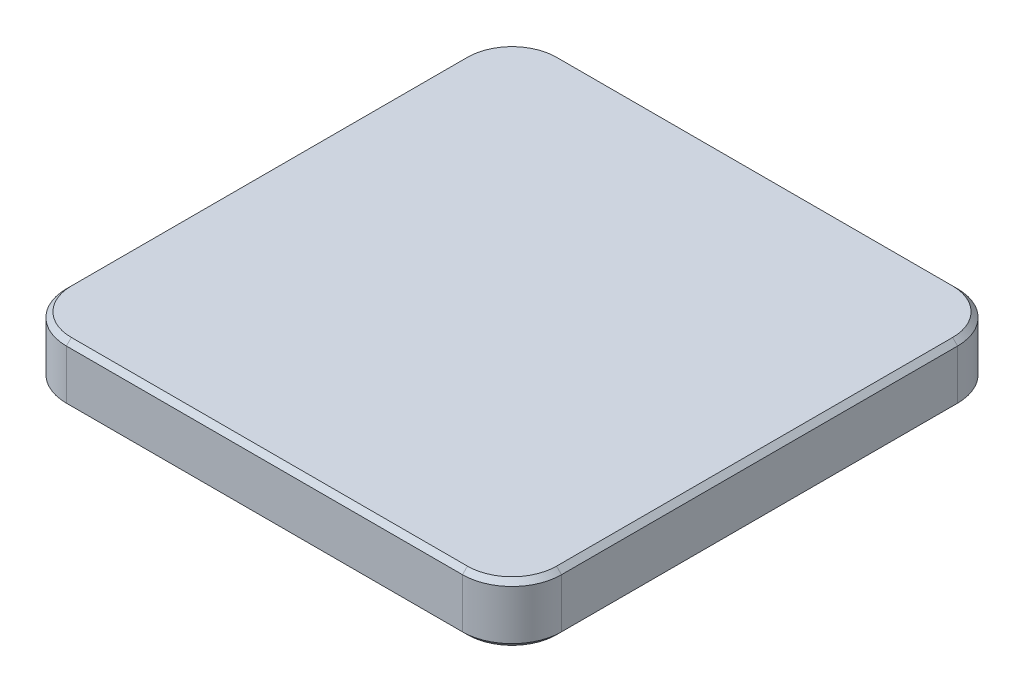
SolidWorks part; units mm, degrees
ref_plane "Front Plane" through (0, 0, 0) normal (0, 0, 1) x (1, 0, 0)
ref_plane "Top Plane" through (0, 0, 0) normal (0, 1, 0) x (1, 0, 0)
ref_plane "Right Plane" through (0, 0, 0) normal (1, 0, 0) x (0, 0, -1)
sketch "Sketch2" plane through (0, 0, 0) normal (0, 1, 0) x (1, 0, 0)
  line L1 (-40, -50) -> (40, -50)
  line L2 (-50, -40) -> (-50, 40)
  line L3 (-40, 50) -> (40, 50)
  line L4 (50, -40) -> (50, 40)
  line L5 (-50, -50) -> (50, 50) construction
  line L6 (-50, 50) -> (50, -50) construction
  arc A0 (-40, -50) -> (-50, -40) centre (-40, -40) cw
  arc A1 (40, -50) -> (50, -40) centre (40, -40) ccw
  arc A2 (40, 50) -> (50, 40) centre (40, 40) cw
  arc A3 (-50, 40) -> (-40, 50) centre (-40, 40) cw
  point P0 (0, 0)
  dimension "D2" = 10
  dimension "D1" = 100
extrude "Boss-Extrude1" add sketch "Sketch2" along normal mid plane 12
chamfer "Chamfer1" distance 1 angle 45 16 edges at (0, -6, 50) (47.0711, -6, 47.0711) (50, -6, 0) (47.0711, -6, -47.0711) (0, -6, -50) (-47.0711, -6, -47.0711) (-50, -6, 0) (-47.0711, -6, 47.0711) (-50, 6, 0) (-47.0711, 6, -47.0711) (0, 6, -50) (47.0711, 6, -47.0711) (50, 6, 0) (47.0711, 6, 47.0711) (0, 6, 50) (-47.0711, 6, 47.0711)
